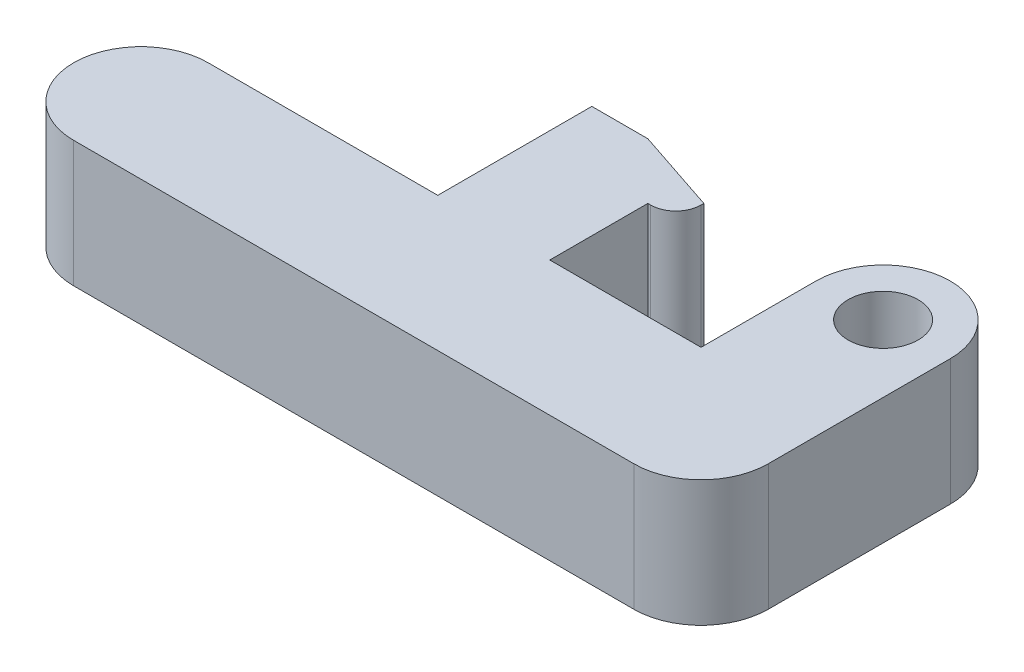
SolidWorks part; units mm, degrees
ref_plane "Front Plane" through (0, 0, 0) normal (0, 0, 1) x (1, 0, 0)
ref_plane "Top Plane" through (0, 0, 0) normal (0, 1, 0) x (1, 0, 0)
ref_plane "Right Plane" through (0, 0, 0) normal (1, 0, 0) x (0, 0, -1)
sketch "Sketch1" plane through (0, 0, 0) normal (0, 1, 0) x (1, 0, 0)
  line L0 (0, 0) -> (0, -6.5) construction
  line L1 (2.4, 0) -> (2.4, -6.5)
  line L2 (-2.4, 0) -> (-2.4, -4.1)
  line L3 (0, -6.5) -> (-20, -6.5) construction
  line L4 (0, -8.9) -> (-20, -8.9)
  line L5 (-2.4, -4.1) -> (-7.8, -4.1)
  line L6 (-7.8, -4.1) -> (-7.8, -0.6)
  line L7 (-7.8, -0.6) -> (-7.7, -0.6)
  line L8 (-9.8, 1.4) -> (-6.8, 0.4)
  line L9 (-9.8, 1.4) -> (-11.8, 1.4)
  line L10 (-11.8, 1.4) -> (-11.8, -4.1)
  line L11 (-6.8, 0.4) -> (-6.8, 0.3)
  line L12 (-11.8, -4.1) -> (-20, -4.1)
  arc A0 (2.4, 0) -> (-2.4, 0) centre (0, 0) ccw
  arc A1 (0, -8.9) -> (2.4, -6.5) centre (0, -6.5) ccw
  arc A2 (0, -8.9) -> (2.4, -6.5) centre (0, -6.5) ccw
  arc A3 (-20, -4.1) -> (-20, -8.9) centre (-20, -6.5) ccw
  circle A4 centre (0, 0) radius 1.25
  arc A5 (-7.7, -0.6) -> (-6.8, 0.3) centre (-7.7, 0.3) ccw
  point P3 (0, 0)
  point P7 (0, 0)
  point P8 (-20, -6.5)
  point P9 (0, 0)
  point P13 (0, 0)
  point P23 (-150.1272, -5)
  point P26 (-20, -5)
  point P29 (-6.8, -0.6)
  dimension "D2" = 2.5
  dimension "D3" = 2.4
  dimension "D6" = 2.4
  dimension "D13" = 0.9
  dimension "D1" = 4
  dimension "D4" = 20
  dimension "D5" = 6.5
  dimension "D7" = 7.8
  dimension "D8" = 3.5
  dimension "D9" = 1
  dimension "D10" = 2
  dimension "D11" = 1
  dimension "D12" = 3
extrude "Boss-Extrude1" add sketch "Sketch1" along normal blind 4.5 contours L12 A3 L4 A1 L1 A0 L2 L5 L6 L7 L11 L8 L9 L10 A4
